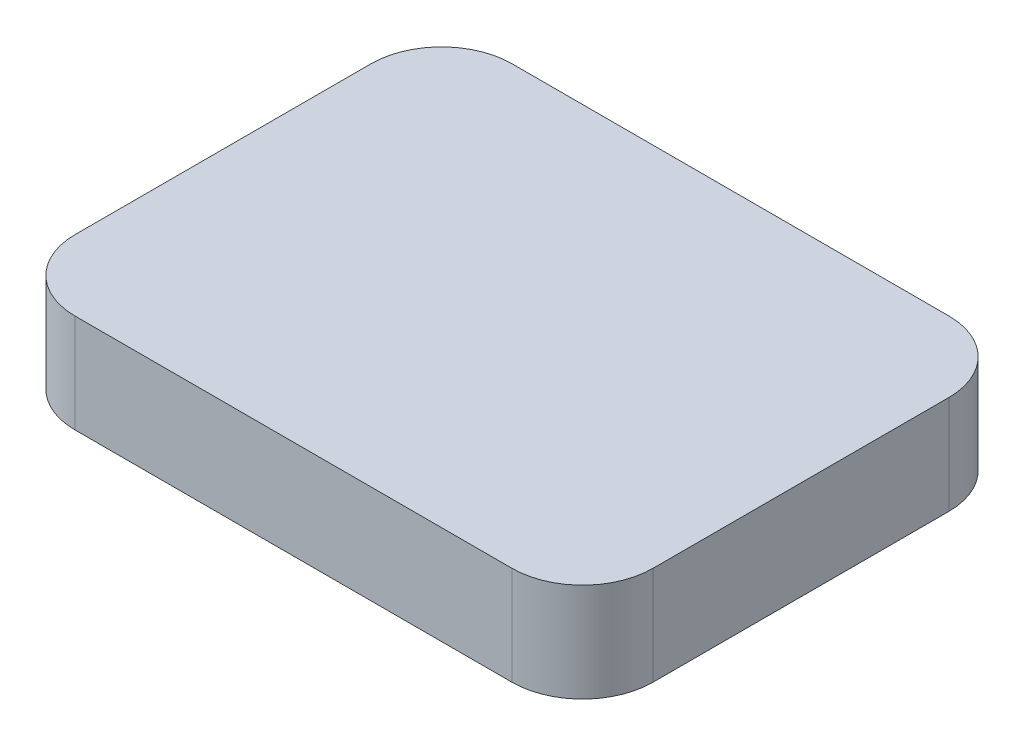
SolidWorks part; units mm, degrees
ref_plane "Front Plane" through (0, 0, 0) normal (0, 0, 1) x (1, 0, 0)
ref_plane "Top Plane" through (0, 0, 0) normal (0, 1, 0) x (1, 0, 0)
ref_plane "Right Plane" through (0, 0, 0) normal (1, 0, 0) x (0, 0, -1)
sketch "Sketch1" plane through (0, 0, 0) normal (0, 1, 0) x (1, 0, 0)
  line L0 (-19.1588, 16.0429) -> (11.8412, 16.0429)
  line L5 (16.8412, 11.0429) -> (16.8412, -9.9571)
  line L6 (-19.1588, -14.9571) -> (11.8412, -14.9571)
  line L7 (-24.1588, 11.0429) -> (-24.1588, -9.9571)
  arc A0 (-19.1588, -14.9571) -> (-24.1588, -9.9571) centre (-19.1588, -9.9571) cw
  arc A1 (16.8412, -9.9571) -> (11.8412, -14.9571) centre (11.8412, -9.9571) cw
  arc A2 (11.8412, 16.0429) -> (16.8412, 11.0429) centre (11.8412, 11.0429) cw
  arc A3 (-19.1588, 16.0429) -> (-24.1588, 11.0429) centre (-19.1588, 11.0429) ccw
  dimension "D4" = 5
extrude "Boss-Extrude1" add sketch "Sketch1" along normal blind 7
sketch "Sketch2" plane through (0, 0, 0) normal (0, -1, 0) x (1, 0, 0)
  line L0 (-24.1588, -11.0429) -> (-24.1588, 9.9571) construction
  line L1 (-19.1588, 9.9571) -> (11.8412, 9.9571)
  line L2 (-19.1588, 9.9571) -> (-19.1588, -11.0429)
  line L3 (-19.1588, -11.0429) -> (11.8412, -11.0429)
  line L4 (11.8412, 9.9571) -> (11.8412, -11.0429)
  line L5 (-19.1588, -16.0429) -> (11.8412, -16.0429) construction
  dimension "D1" = 31
  dimension "D2" = 21
  dimension "D3" = 5
  dimension "D4" = 5
extrude "Cut-Extrude1" cut sketch "Sketch2" against normal blind 5 and the other way blind 4 contours L2 L1 L4 L3
